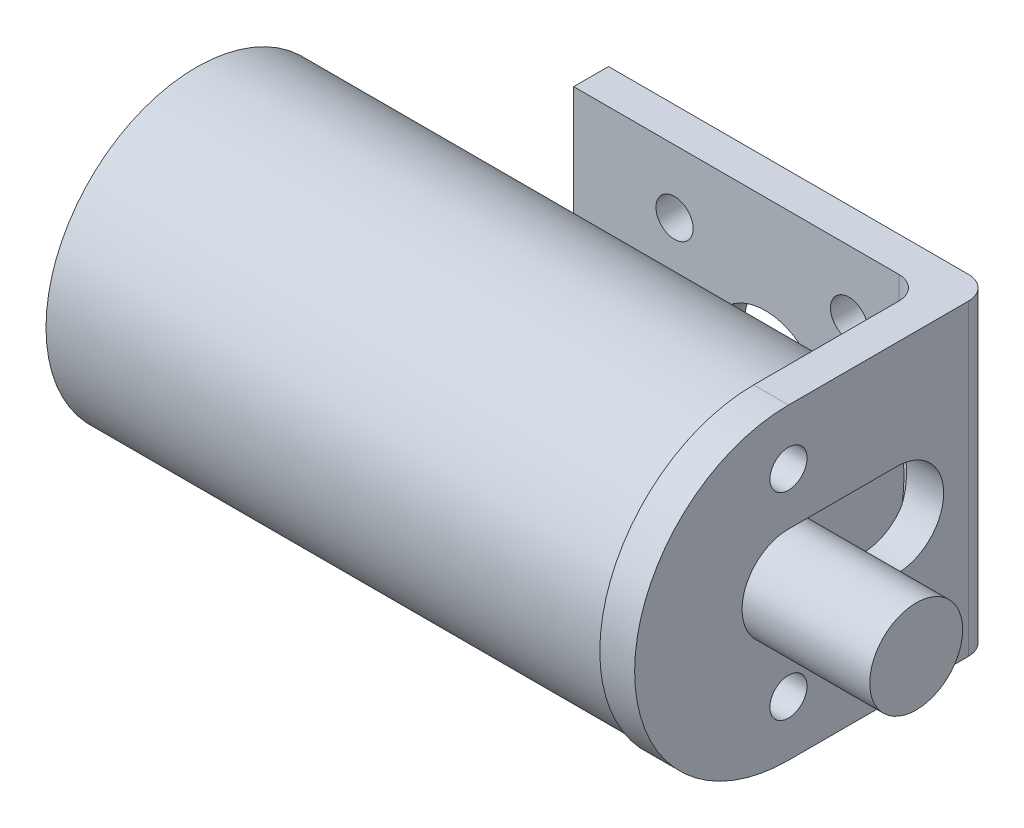
SolidWorks part; units mm, degrees
ref_plane "Front Plane" through (0, 0, 0) normal (0, 0, 1) x (1, 0, 0)
ref_plane "Top Plane" through (0, 0, 0) normal (0, 1, 0) x (1, 0, 0)
ref_plane "Right Plane" through (0, 0, 0) normal (1, 0, 0) x (0, 0, -1)
other "Configuration Table"
sketch "草图2" plane through (0, 0, 0) normal (0, 1, 0) x (1, 0, 0)
  line L0 (-23.472, 6.4976) -> (-23.472, 3.4976)
  line L1 (-23.472, 3.4976) -> (4.528, 3.4976)
  line L2 (6.528, 1.4976) -> (6.528, -26.5024)
  line L3 (6.528, -26.5024) -> (9.528, -26.5024)
  line L4 (9.528, -26.5024) -> (9.528, 4.4976)
  line L6 (7.528, 6.4976) -> (-23.472, 6.4976)
  arc A0 (6.528, 1.4976) -> (4.528, 3.4976) centre (4.528, 1.4976) ccw
  arc A1 (9.528, 4.4976) -> (7.528, 6.4976) centre (7.528, 4.4976) ccw
  dimension "D5" = 2
  dimension "D6" = 2
  dimension "D1" = 33
  dimension "D2" = 3
  dimension "D3" = 3
  dimension "D4" = 33
extrude "凸台-拉伸1" add sketch "草图2" along normal blind 26.5
sketch "草图4" plane through (0, 0, -6.4976) normal (0, 0, -1) x (-1, 0, 0)
  line L0 (-7.528, 26.5) -> (23.472, 26.5) construction
  line L1 (-0.2446, 21.0549) -> (14.7885, 21.0549) construction
  line L2 (23.472, 26.5) -> (23.472, 0) construction
  circle A0 centre (6.972, 13.25) radius 4.8
  circle A1 centre (-0.2446, 21.0549) radius 1.6
  circle A2 centre (14.7885, 21.0549) radius 1.6
  circle A3 centre (14.7885, 6.0218) radius 1.6
  circle A4 centre (-0.2446, 6.0218) radius 1.6
  point P17 (7.2719, 13.5384)
  dimension "D1" = 9.6
  dimension "D2" = 3.2
  dimension "D3" = 13.25
  dimension "D4" = 16.5
  dimension "D5" = 10.63
  dimension "D6" = 4
extrude "切除-拉伸1" cut sketch "草图4" against normal blind 26
sketch "草图5" plane through (9.528, 0, 0) normal (1, 0, 0) x (0, 0, -1)
  line L2 (-26.5024, 26.5) -> (-26.5024, 0) construction
  line L4 (1.4976, 26.5) -> (-26.5024, 26.5) construction
  line L5 (-11.0024, 9.25) -> (-1.6372, 9.25)
  line L9 (-14.8344, 12.1031) -> (-5.2474, 14.9724) construction
  line L10 (2.3628, 9.25) -> (1.6913, 9.451) construction
  line L11 (-11.0024, 17.25) -> (-1.6372, 17.25)
  line L12 (1.6294, 17.25) -> (2.3628, 17.25)
  line L13 (1.6913, 17.049) -> (2.3628, 17.25) construction
  line L14 (-11.0024, 21.75) -> (-11.0024, 13.25) construction
  line L15 (-26.5024, 0) -> (4.4976, 0)
  line L16 (4.4976, 0) -> (4.4976, 26.5)
  line L17 (4.4976, 26.5) -> (-26.5024, 26.5)
  line L18 (-26.5024, 26.5) -> (-26.5024, 0)
  line L19 (-26.5024, 0) -> (-11.0024, 0)
  line L21 (-11.0024, 26.5) -> (-26.5024, 26.5)
  line L22 (-26.5024, 26.5) -> (-26.5024, 0)
  line L23 (1.6294, 9.25) -> (2.3628, 9.25)
  line L24 (-11.0024, 13.25) -> (-14.8344, 14.3969) construction
  line L25 (4.4976, 26.5) -> (4.4976, 0) construction
  arc A0 (-11.0024, 17.25) -> (-11.0024, 9.25) centre (-11.0024, 13.25) ccw
  arc A1 (-11.0024, 26.5) -> (-11.0024, 0) centre (-11.0024, 13.25) ccw
  arc A2 (1.6294, 9.25) -> (1.6913, 9.451) centre (-11.0024, 13.25) ccw
  arc A3 (1.6913, 17.049) -> (1.6294, 17.25) centre (-11.0024, 13.25) ccw
  arc A4 (-1.6372, 9.25) -> (-1.6372, 17.25) centre (-1.6372, 13.25) ccw
  circle A5 centre (-11.0024, 21.75) radius 1.6
  circle A6 centre (-11.0024, 4.75) radius 1.6
  line M1 (-26.5024, 0) -> (4.4976, 0)
  line M3 (4.4976, 26.5) -> (-26.5024, 26.5)
  line M4 (-26.5024, 26.5) -> (-26.5024, 0)
  dimension "D1" = 8
  dimension "D3" = 13.25
  dimension "D5" = 8
  dimension "D6" = 3.2
  dimension "D7" = 8.5
  dimension "D2" = 15.5
  dimension "D4" = 0
  dimension "D8" = 2
extrude "切除-拉伸2" cut sketch "草图5" against normal blind 26 contours A1 M3 M4 M1 | L5 A4 L11 A0 | A6 | A5
sketch "草图6" plane through (6.528, 0, 0) normal (-1, 0, 0) x (0, 0, 1)
  circle A0 centre (11.0024, 13.25) radius 12.95
  arc A1 (11.0024, 0) -> (11.0024, 26.5) centre (11.0024, 13.25) ccw construction
  dimension "D1" = 25.9
extrude "凸台-拉伸2" add sketch "草图6" along normal blind 48
sketch "草图7" plane through (6.528, 0, 0) normal (1, 0, 0) x (0, 0, -1)
  circle A0 centre (-11.0024, 13.25) radius 4
  dimension "D1" = 8
extrude "凸台-拉伸3" add sketch "草图7" along normal blind 14
